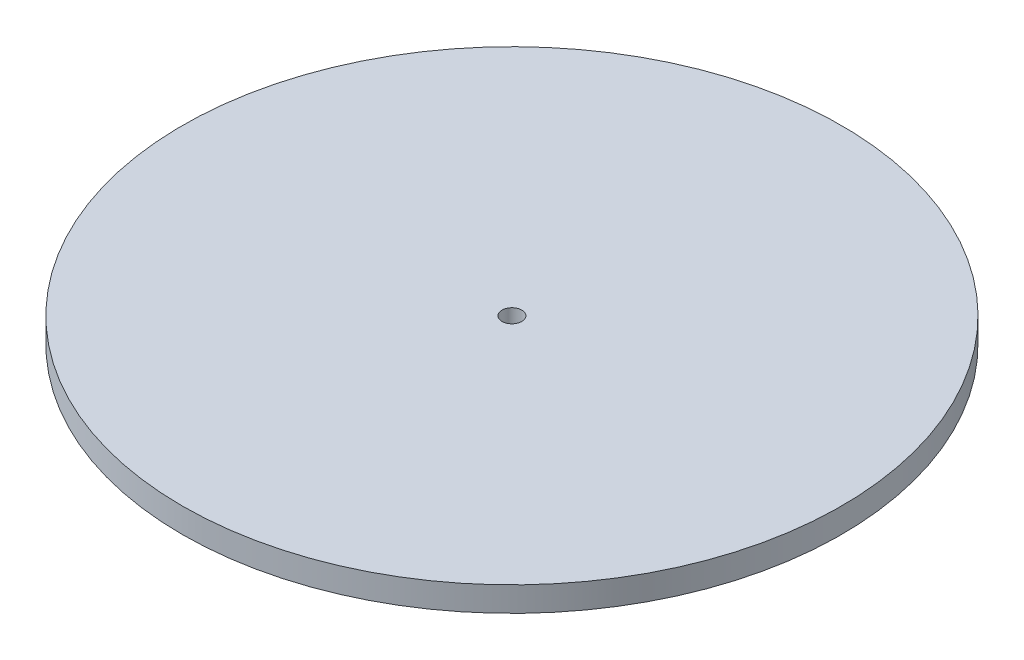
SolidWorks part; units mm, degrees
ref_plane "Front Plane" through (0, 0, 0) normal (0, 0, 1) x (1, 0, 0)
ref_plane "Top Plane" through (0, 0, 0) normal (0, 1, 0) x (1, 0, 0)
ref_plane "Right Plane" through (0, 0, 0) normal (1, 0, 0) x (0, 0, -1)
sketch "Sketch3" plane through (0, 0, 0) normal (0, 0, 1) x (1, 0, 0)
  line L0 (37, 22.1737) -> (37, 26.1737) construction
  line L1 (37, 26.1737) -> (0, 26.1737) construction
  line L2 (0, 26.1737) -> (0, 0) construction
  line L4 (1.2, 26.1737) -> (1.2, 21.1737)
  line L5 (1.2, 21.1737) -> (0, 21.1737)
  line L6 (0, 21.1737) -> (0, 0)
  line L7 (37, 22.1737) -> (40, 22.1737) construction
  line L8 (40, 22.1737) -> (40, 26.1737) construction
  line L9 (40, 26.1737) -> (1.2, 26.1737)
  line L10 (37, 22.1737) -> (37, 23.1737)
  line L11 (37, 23.1737) -> (40, 23.1737)
  line L12 (40, 23.1737) -> (40, 26.1737)
  spline S0 degree 8 poles (-3.303, 2.0321) (2.1818, -6.7622) (7.6666, 12.5363) (13.1515, -0.5283) (18.6363, 19.3438) (24.1211, 9.6561) (29.6059, 21.3183) (35.0907, 19.7784) (40.5756, 24.5711) knots 0 0 0 0 0 0 0 0 0 1 1 1 1 1 1 1 1 1 construction
  spline S1 degree 8 poles (0, 0) (4.625, 0.3635) (9.25, 7.5093) (13.875, 6.1319) (18.5, 13.6328) (23.125, 13.1943) (27.75, 17.6095) (32.375, 19.5837) (37, 22.1737) knots 0.075276 0.075276 0.075276 0.075276 0.075276 0.075276 0.075276 0.075276 0.075276 0.918512 0.918512 0.918512 0.918512 0.918512 0.918512 0.918512 0.918512 0.918512
  dimension "D1" = 3
  dimension "D2" = 1.2
  dimension "D3" = 5
  dimension "D4" = 3
  dimension "D5" = 40
  dimension "D6" = 22.1737
  dimension "D7" = 37
  dimension "D8" = 4
revolve "Revolve4" add sketch "Sketch3" angle 360 about L2
sketch "Sketch5" plane through (0, 26.1737, 0) normal (0, 1, 0) x (1, 0, 0)
  circle A0 centre (0, 0) radius 1.2
  circle A2 centre (0, 0) radius 1.2 construction
extrude "Cut-Extrude1" cut sketch "Sketch5" against normal through all
ref_plane "Plane1" through (0, 0.2672, 0) normal (0, -1, 0) x (-1, 0, 0)
sketch "Sketch6" plane through (0, 0.2672, 0) normal (0, -1, 0) x (-1, 0, 0)
  circle A0 centre (0, 0) radius 1.2 construction
  point P0 (0, 0)
